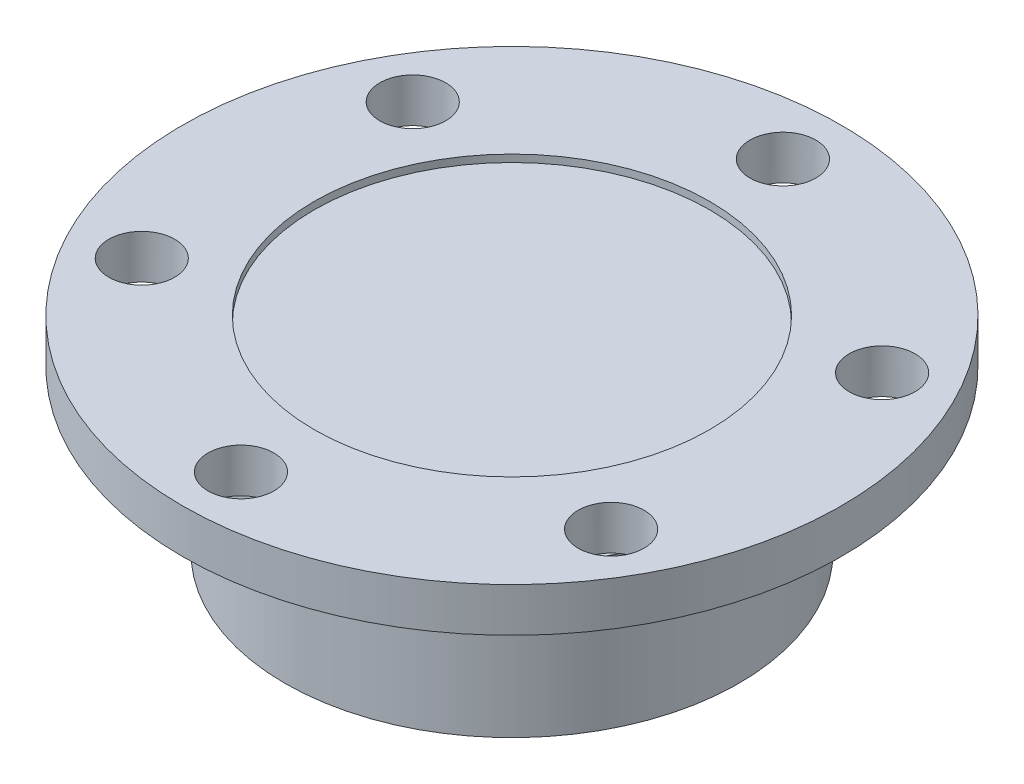
SolidWorks part; units mm, degrees
ref_plane "Front Plane" through (0, 0, 0) normal (0, 0, 1) x (1, 0, 0)
ref_plane "Top Plane" through (0, 0, 0) normal (0, 1, 0) x (1, 0, 0)
ref_plane "Right Plane" through (0, 0, 0) normal (1, 0, 0) x (0, 0, -1)
sketch "Sketch1" plane through (0, 0, 0) normal (0, 0, 1) x (1, 0, 0)
  line L0 (0, 30.6188) -> (0, -35.2308) construction
  line L2 (-45, 28) -> (-45, 22)
  line L3 (-45, 22) -> (-29.5, 22)
  line L4 (-29.5, 22) -> (-29.5, 20.5)
  line L5 (-29.5, 20.5) -> (-31, 20.5)
  line L6 (-31, 20.5) -> (-31, 0)
  line L7 (-31, 0) -> (-26.32, 0)
  line L8 (-26.32, 0) -> (-22, 24.5)
  line L9 (-22, 24.5) -> (0, 24.5)
  line L11 (-45, 28) -> (-27, 28)
  line L12 (-27, 28) -> (-27, 27)
  line L13 (-27, 27) -> (0, 27)
  line L14 (0, 27) -> (0, 24.5)
  dimension "D1" = 31
  dimension "D2" = 45
  dimension "D3" = 18
  dimension "D4" = 100
  dimension "D5" = 1.5
  dimension "D6" = 15.5
  dimension "D7" = 1.5
  dimension "D8" = 22
  dimension "D9" = 22
  dimension "D10" = 1
  dimension "D11" = 2.5
  dimension "D12" = 6
revolve "Revolve1" add sketch "Sketch1" angle 360 about L0
sketch "Sketch2" plane through (0, 28, 0) normal (0, 1, 0) x (1, 0, 0)
  line L0 (-53.4517, 0) -> (69.7526, 0) construction
  line L1 (0, 51.0634) -> (0, -55.84) construction
  circle A0 centre (0, 37) radius 4.5
  circle A1 centre (32.0429, 18.5) radius 4.5
  circle A2 centre (32.0429, -18.5) radius 4.5
  circle A3 centre (0, -37) radius 4.5
  circle A4 centre (-32.0429, -18.5) radius 4.5
  circle A5 centre (-32.0429, 18.5) radius 4.5
  point P19 (0, 0)
  dimension "D1" = 9
  dimension "D2" = 37
  dimension "D3" = 6
extrude "Cut-Extrude1" cut sketch "Sketch2" against normal up to next
